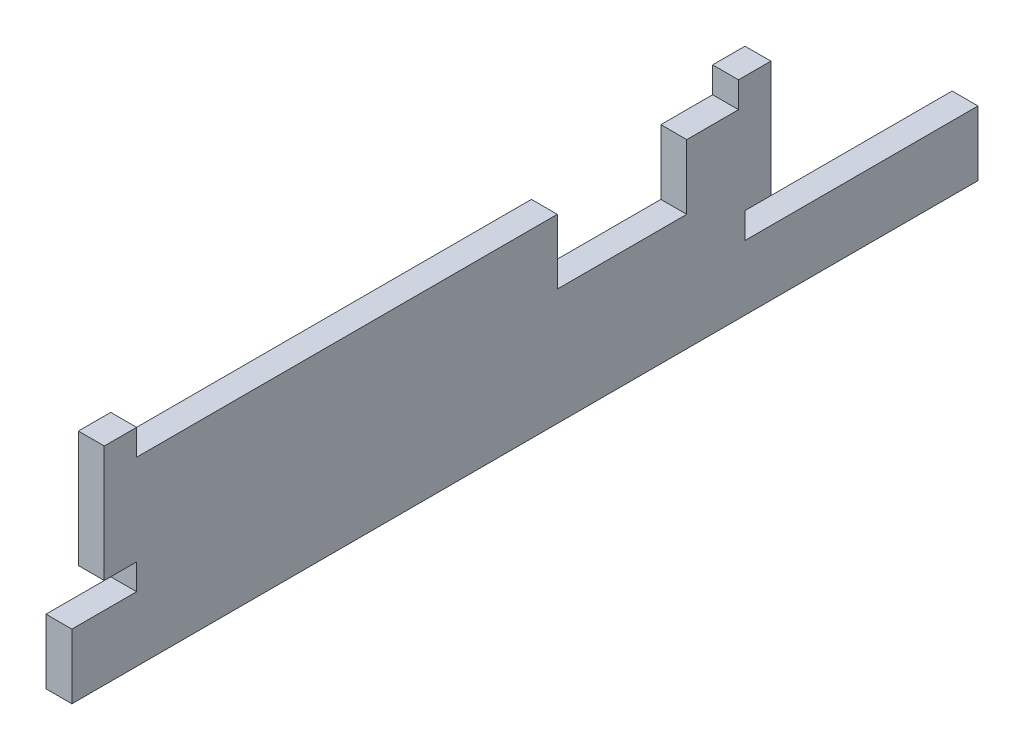
SolidWorks part; units mm, degrees
material "Beech"
ref_plane "Front Plane" through (0, 0, 0) normal (0, 0, 1) x (1, 0, 0)
ref_plane "Top Plane" through (0, 0, 0) normal (0, 1, 0) x (1, 0, 0)
ref_plane "Right Plane" through (0, 0, 0) normal (1, 0, 0) x (0, 0, -1)
sketch "Sketch1" plane through (0, 0, 0) normal (1, 0, 0) x (0, 0, -1)
  line L10 (-95.831, 23.3448) -> (-95.831, 5.3448)
  line L11 (-95.831, 5.3448) -> (-90.831, 5.3448)
  line L12 (-90.831, 5.3448) -> (-90.831, 1.3448)
  line L13 (-90.831, 1.3448) -> (-100.831, 1.3448)
  line L14 (-100.831, 1.3448) -> (-100.831, -8.6552)
  line L16 (-90.831, 19.3448) -> (-90.831, 23.3448)
  line L17 (-90.831, 23.3448) -> (-95.831, 23.3448)
  line L18 (2.169, 19.3448) -> (2.169, 23.3448)
  line L19 (2.169, 23.3448) -> (7.169, 23.3448)
  line L20 (7.169, 23.3448) -> (7.169, 5.3448)
  line L21 (7.169, 5.3448) -> (3.169, 5.3448)
  line L22 (3.169, 5.3448) -> (3.169, 1.3448)
  line L23 (3.169, 1.3448) -> (39.169, 1.3448)
  line L24 (39.169, 1.3448) -> (39.169, -8.6552)
  line L25 (-100.831, -8.6552) -> (39.169, -8.6552)
  line L26 (-90.831, 19.3448) -> (-25.831, 19.3448)
  line L27 (-25.831, 19.3448) -> (-25.831, 9.3448)
  line L28 (-25.831, 9.3448) -> (-5.831, 9.3448)
  line L29 (-5.831, 9.3448) -> (-5.831, 19.3448)
  line L30 (-5.831, 19.3448) -> (2.169, 19.3448)
  dimension "D2" = 8
  dimension "D3" = 20
  dimension "D4" = 10
  dimension "D5" = 45
  dimension "D8" = 4
  dimension "D9" = 5
  dimension "D10" = 5
  dimension "D11" = 18
  dimension "D12" = 10
  dimension "D13" = 10
  dimension "D14" = 93
  dimension "D15" = 5
  dimension "D16" = 140
  dimension "D17" = 4
extrude "Boss-Extrude1" add sketch "Sketch1" along normal blind 4
